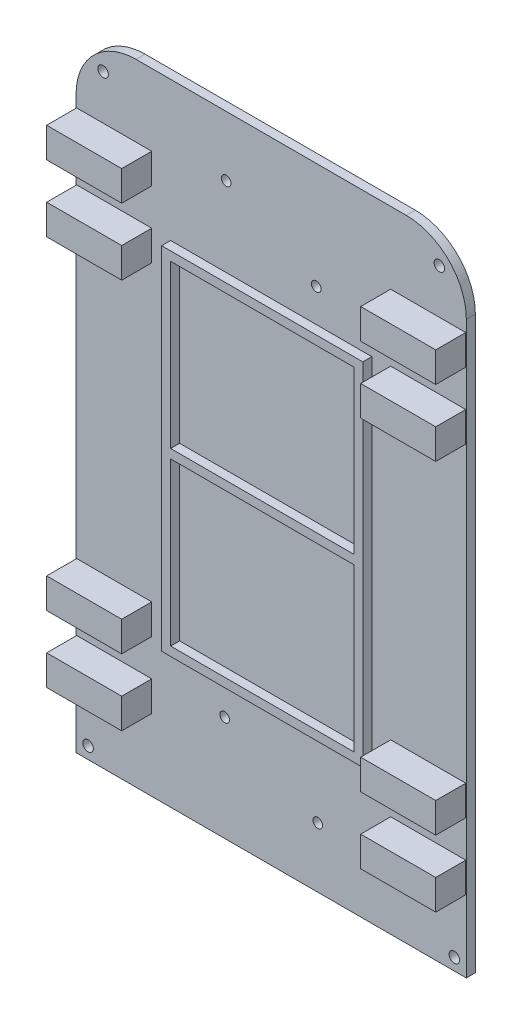
SolidWorks part; units mm, degrees
ref_plane "Front Plane" through (0, 0, 0) normal (0, 0, 1) x (1, 0, 0)
ref_plane "Top Plane" through (0, 0, 0) normal (0, 1, 0) x (1, 0, 0)
ref_plane "Right Plane" through (0, 0, 0) normal (1, 0, 0) x (0, 0, -1)
sketch "Sketch1" plane through (0, 0, 0) normal (0, 0, 1) x (1, 0, 0)
  line L1 (-65, 105) -> (65, 105)
  line L2 (-65, 105) -> (-65, -105)
  line L3 (-65, -105) -> (65, -105)
  line L4 (65, 105) -> (65, -105)
  line L5 (-65, 105) -> (65, -105) construction
  line L6 (-65, -105) -> (65, 105) construction
  point P0 (0, 0)
  dimension "D1" = 210
  dimension "D2" = 130
extrude "Boss-Extrude1" add sketch "Sketch1" along normal blind 3
fillet "Fillet1" radius 20 1 edges at (-65, 105, 1.5)
fillet "Fillet2" radius 20 1 edges at (65, 105, 1.5)
sketch "Sketch2" plane through (0, 0, 3) normal (0, 0, 1) x (1, 0, 0)
  line L0 (-65, -65) -> (65, -65) construction
  line L1 (-65, 85) -> (-65, -105) construction
  line L2 (65, -105) -> (65, 85) construction
  line L3 (65, 65) -> (-65, 65) construction
  line L4 (-65, -105) -> (65, -105) construction
  line L5 (45, 105) -> (-45, 105) construction
  line L6 (0, 105) -> (0, -105) construction
  line L7 (64.8, 58.9) -> (39.8, 58.9)
  line L9 (64.8, 48.9) -> (39.8, 48.9)
  line L10 (39.8, 58.9) -> (39.8, 48.9)
  line L11 (64.8, 71.1) -> (39.8, 71.1)
  line L13 (64.8, 81.1) -> (39.8, 81.1)
  line L14 (39.8, 71.1) -> (39.8, 81.1)
  line L15 (-65, 0) -> (65, 0) construction
  line L16 (64.8, 71.1) -> (64.8, 81.1)
  line L17 (64.8, 48.9) -> (64.8, 58.9)
  dimension "D1" = 40
  dimension "D2" = 40
  dimension "D4" = 10
  dimension "D6" = 10
  dimension "D7" = 6.1
  dimension "D8" = 6.1
extrude "Boss-Extrude2" add sketch "Sketch2" along normal blind 10
mirror "Mirror1" about plane through (0, 0, 0) normal (0, 1, 0) of "Boss-Extrude2"
mirror "Mirror2" about plane through (0, 0, 0) normal (1, 0, 0) of "Mirror1", "Boss-Extrude2"
sketch "Sketch3" plane through (0, 0, 3) normal (0, 0, 1) x (1, 0, 0)
  line L1 (30.5, 55.5) -> (-30.5, 55.5)
  line L2 (30.5, 55.5) -> (30.5, 1.5)
  line L3 (30.5, 1.5) -> (-30.5, 1.5)
  line L4 (-30.5, 55.5) -> (-30.5, 1.5)
  line L5 (0, 105) -> (0, -105) construction
  line L6 (45, 105) -> (-45, 105) construction
  line L7 (-65, -105) -> (65, -105) construction
  line L8 (33.5, 58.5) -> (-33.5, 58.5)
  line L9 (33.5, 58.5) -> (33.5, -1.5)
  line L10 (33.5, -1.5) -> (-33.5, -1.5)
  line L11 (-33.5, 58.5) -> (-33.5, -1.5)
  line L12 (33.5, 58.5) -> (-33.5, -1.5) construction
  line L13 (33.5, -1.5) -> (-33.5, 58.5) construction
  point P4 (0, 55.5)
  point P5 (0, 28.5)
  dimension "D1" = 54
  dimension "D2" = 61
  dimension "D3" = 49.5
  dimension "D4" = 3
  dimension "D5" = 3
  dimension "D6" = 3
extrude "Boss-Extrude3" add sketch "Sketch3" along normal blind 3
mirror "Mirror3" about plane through (0, 0, 0) normal (0, 1, 0) of "Boss-Extrude3"
sketch "Croquis1" plane through (0, 0, 3) normal (0, 0, 1) x (1, 0, 0)
  line L0 (15, 77.25) -> (65, 77.25) construction
  line L2 (-15, 77.25) -> (-65, 77.25) construction
  line L4 (45, 105) -> (-45, 105) construction
  line L5 (-65, 85) -> (-65, -105) construction
  line L8 (65, -105) -> (65, 85) construction
  line L9 (-15.5, -77.5) -> (-65, -77.5) construction
  line L10 (-15.5, -70) -> (15.5, -70) construction
  line L11 (-15.5, -70) -> (-15.5, -85) construction
  line L12 (-15.5, -85) -> (15.5, -85) construction
  line L13 (15.5, -70) -> (15.5, -85) construction
  line L14 (15.5, -77.5) -> (65, -77.5) construction
  line L16 (-15, 85) -> (15, 85) construction
  line L17 (-15, 85) -> (-15, 69.5) construction
  line L18 (-15, 69.5) -> (15, 69.5) construction
  line L19 (15, 85) -> (15, 69.5) construction
  line L20 (-65, -105) -> (65, -105) construction
  circle A0 centre (-15, 85) radius 1.6
  circle A1 centre (15, 69.5) radius 1.6
  circle A2 centre (-15.5, -70) radius 1.6
  circle A3 centre (15.5, -85) radius 1.6
  dimension "D4" = 3.2
  dimension "D12" = 3.2
  dimension "D13" = 3.2
  dimension "D14" = 3.2
  dimension "D2" = 50
  dimension "D3" = 50
  dimension "D5" = 31
  dimension "D6" = 15
  dimension "D7" = 49.5
  dimension "D8" = 49.5
  dimension "D9" = 20
  dimension "D10" = 30
  dimension "D11" = 15.5
  dimension "D15" = 20
extrude "Cortar-Extruir1" cut sketch "Croquis1" against normal blind 10
sketch "Croquis2" plane through (0, 0, 3) normal (0, 0, 1) x (1, 0, 0)
  line L0 (-65, 85) -> (-65, -105) construction
  line L1 (-65, -105) -> (65, -105) construction
  line L2 (65, -105) -> (65, 85) construction
  line L3 (45, 105) -> (-45, 105) construction
  circle A0 centre (-61, -101) radius 1.75
  circle A1 centre (61, -101) radius 1.75
  circle A2 centre (56, 96) radius 1.75
  circle A3 centre (-56, 96) radius 1.75
  dimension "D1" = 4
  dimension "D3" = 3.5
  dimension "D4" = 4
  dimension "D5" = 4
  dimension "D6" = 3.5
  dimension "D7" = 9
  dimension "D9" = 3.5
  dimension "D10" = 9
  dimension "D11" = 9
  dimension "D12" = 3.5
  dimension "D2" = 4
  dimension "D8" = 9
extrude "Cortar-Extruir2" cut sketch "Croquis2" against normal blind 10
